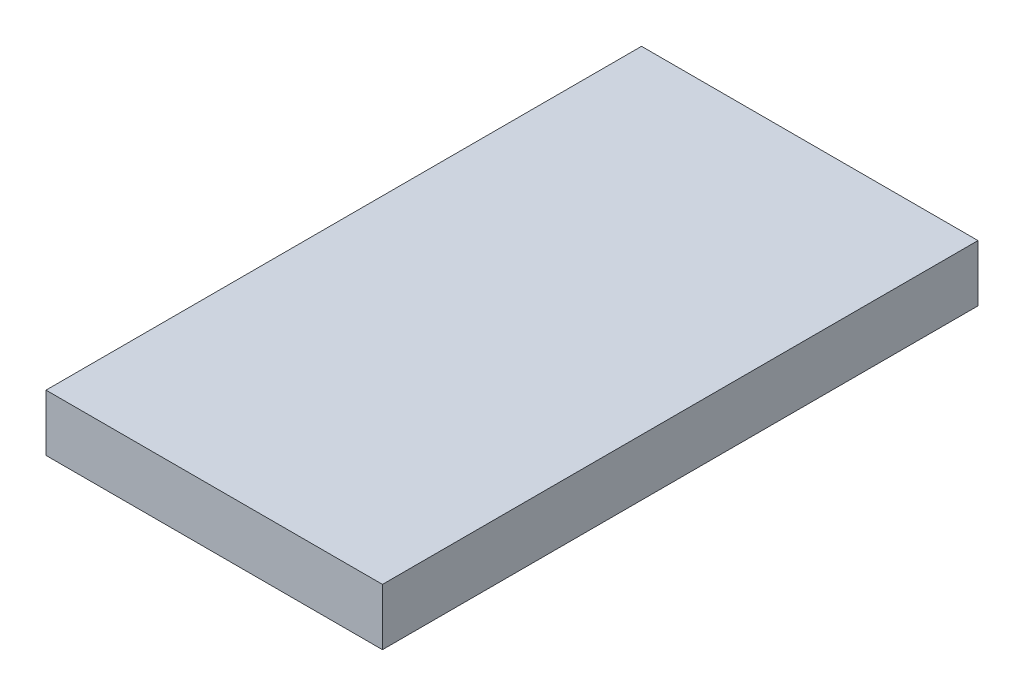
SolidWorks part; units mm, degrees
material "Plastique personnalisé"
ref_plane "Plan de face" through (0, 0, 0) normal (0, 0, 1) x (1, 0, 0)
ref_plane "Plan de dessus" through (0, 0, 0) normal (0, 1, 0) x (1, 0, 0)
ref_plane "Plan de droite" through (0, 0, 0) normal (1, 0, 0) x (0, 0, -1)
sketch "Esquisse1" plane through (0, 0, 0) normal (0, 0, 1) x (1, 0, 0)
  line L0 (-23.0431, 21.298) -> (-23.0431, 30.798)
  line L1 (-23.0431, 30.798) -> (33.4569, 30.798)
  line L2 (33.4569, 30.798) -> (33.4569, 21.298)
  line L3 (33.4569, 21.298) -> (-23.0431, 21.298)
  dimension "D1" = 56.5
  dimension "D2" = 9.5
extrude "Boss.-Extru.1" add sketch "Esquisse1" along normal blind 100
